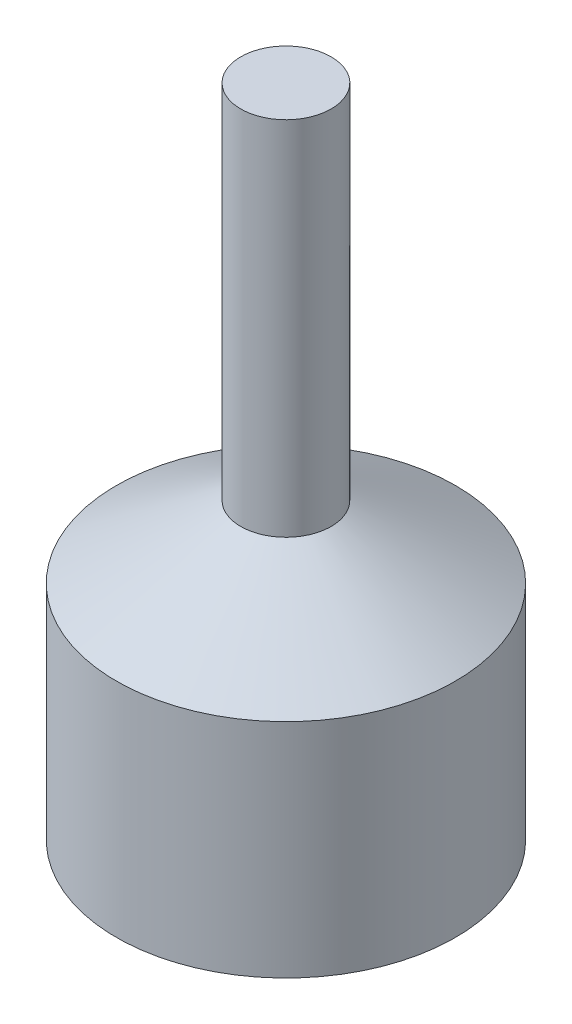
SolidWorks part; units mm, degrees
ref_plane "Front" through (0, 0, 0) normal (0, 0, 1) x (1, 0, 0)
ref_plane "Top" through (0, 0, 0) normal (0, 1, 0) x (1, 0, 0)
ref_plane "Right" through (0, 0, 0) normal (1, 0, 0) x (0, 0, -1)
sketch "Sketch1" plane through (0, 0, 0) normal (1, 0, 0) x (0, 0, -1)
  line L0 (0, 0) -> (0, 100.848) construction
  line L1 (0, 95.25) -> (6.35, 95.25)
  line L2 (6.35, 95.25) -> (6.35, 44.45)
  line L3 (6.35, 44.45) -> (23.8125, 34.368)
  line L4 (23.8125, 34.368) -> (23.8125, 3.175)
  line L5 (23.8125, 3.175) -> (19.05, 3.175)
  line L6 (19.05, 3.175) -> (19.05, 0)
  line L7 (19.05, 0) -> (0, 0)
  line L8 (0, 0) -> (0, 95.25)
  dimension "D1" = 47.625
  dimension "D2" = 38.1
  dimension "D3" = 3.175
  dimension "D4" = 12.7
  dimension "D5" = 95.25
  dimension "D6" = 50.8
  dimension "D7" = 60
revolve "Revolve1" add sketch "Sketch1" angle 360 about L0
cosmetic thread "Cosmetic Thread1"
